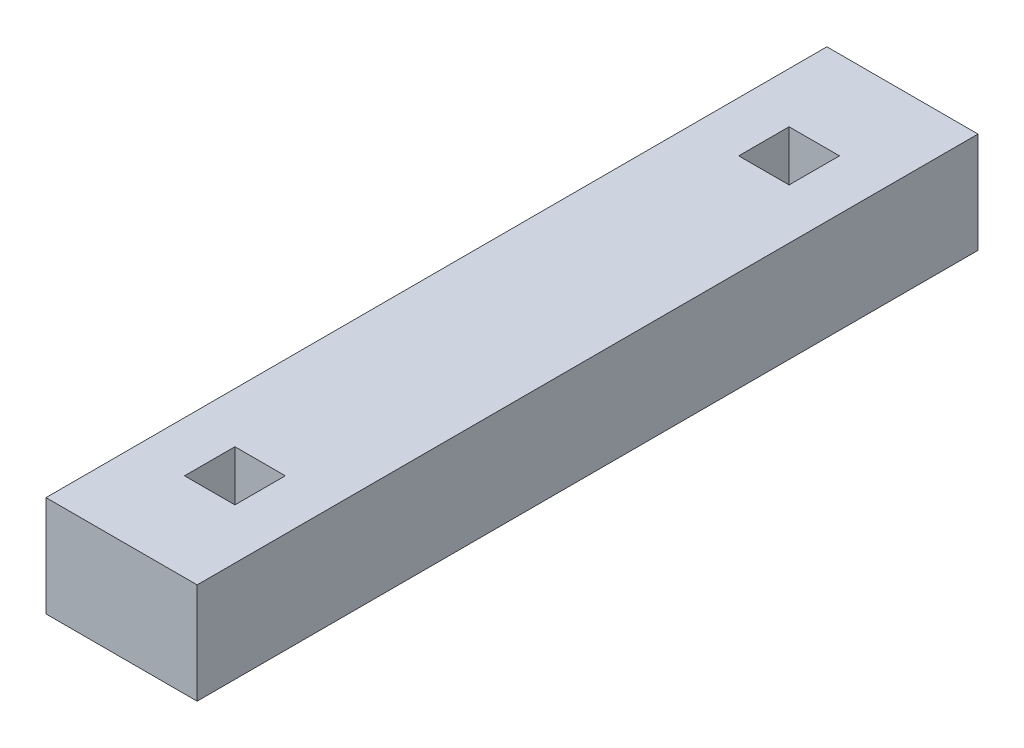
SolidWorks part; units mm, degrees
ref_plane "Front Plane" through (0, 0, 0) normal (0, 0, 1) x (1, 0, 0)
ref_plane "Top Plane" through (0, 0, 0) normal (0, 1, 0) x (1, 0, 0)
ref_plane "Right Plane" through (0, 0, 0) normal (1, 0, 0) x (0, 0, -1)
sketch "Sketch1" plane through (0, 0, 0) normal (0, 1, 0) x (1, 0, 0)
  line L0 (0, 72.5) -> (0, -82.5) construction
  line L1 (-15, 72.5) -> (15, 72.5)
  line L2 (-15, 72.5) -> (-15, -82.5)
  line L3 (-15, -82.5) -> (15, -82.5)
  line L4 (15, 72.5) -> (15, -82.5)
  line L5 (-5, 55) -> (5, 55)
  line L6 (-5, 55) -> (-5, 45)
  line L7 (-5, 45) -> (5, 45)
  line L8 (5, 55) -> (5, 45)
  line L9 (15, -5) -> (-15, -5) construction
  line L10 (-5, -65) -> (-5, -55)
  line L11 (-5, -55) -> (5, -55)
  line L12 (5, -65) -> (5, -55)
  line L13 (-5, -65) -> (5, -65)
  point P9 (0, 55)
  point P10 (0, 72.5)
  dimension "D3" = 10
  dimension "D5" = 100
  dimension "D4" = 10
  dimension "D1" = 30
  dimension "D2" = 155
extrude "Boss-Extrude1" add sketch "Sketch1" along normal blind 20
